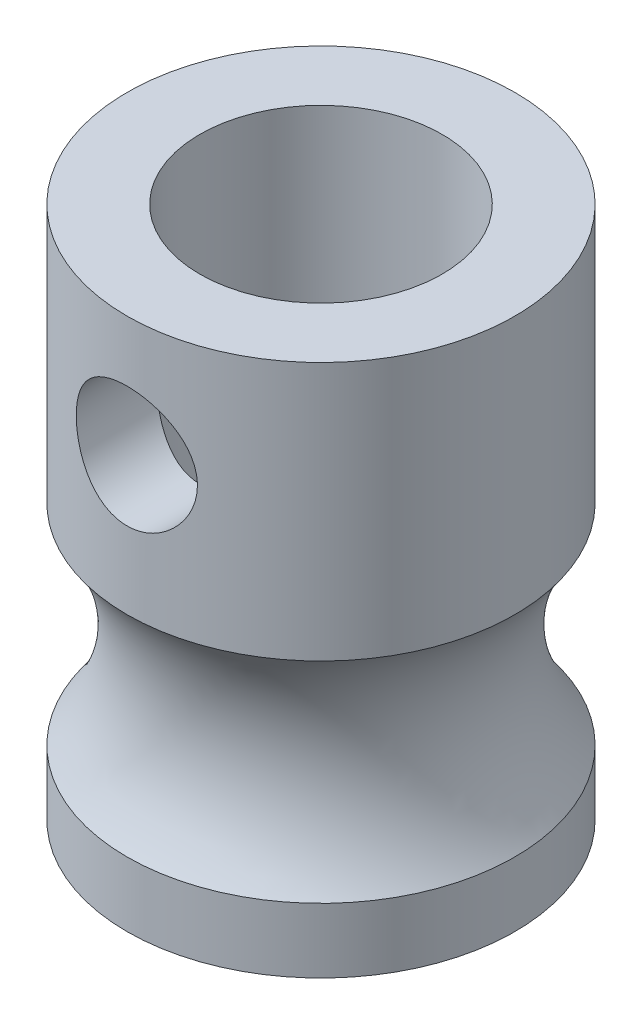
SolidWorks part; units mm, degrees
ref_plane "Front Plane" through (0, 0, 0) normal (0, 0, 1) x (1, 0, 0)
ref_plane "Top Plane" through (0, 0, 0) normal (0, 1, 0) x (1, 0, 0)
ref_plane "Right Plane" through (0, 0, 0) normal (1, 0, 0) x (0, 0, -1)
sketch "Sketch1" plane through (0, 0, 0) normal (0, 1, 0) x (1, 0, 0)
  circle A0 centre (0, 0) radius 4
  circle A1 centre (0, 0) radius 2.5
  dimension "D1" = 8
  dimension "D2" = 5
extrude "Boss-Extrude1" add sketch "Sketch1" along normal blind 11
ref_plane "Plane1" through (0, 0, 4) normal (0, 0, 1) x (1, 0, 0)
ref_axis "Axis1" through (0, 11, 0) along (0, -1, 0)
hole_wizard "M3 Tapped Hole1" positions "Sketch6" profile "Sketch7" tap size "M3" standard "ISO"
sketch "Sketch6" plane through (0, 0, 4) normal (0, 0, 1) x (1, 0, 0)
  line L0 (4, 11) -> (-4, 11) construction
  line L1 (0, 11) -> (0, 0) construction
  point P1 (0, 8.5)
  dimension "D1" = 2.5
cosmetic thread "Hole Thread1" parameters "D2"=3
sketch "Sketch7" plane through (0, 8.5, 4) normal (1, 0, 0) x (0, -1, 0)
  line L0 (0, 0) -> (0, 1.5)
  line L1 (0, 1.5) -> (1.25, 1.5)
  line L2 (1.25, 1.5) -> (1.25, 0)
  line L5 (1.25, 0) -> (0, 0)
  line L11 (0, -6.35) -> (0, 107.95) construction
  dimension "Thru Tap Drill Dia." = 2.5
  dimension "Thru Tap Drill Depth" = 1.5
ref_plane "Plane3" through (0, 0, 0) normal (0, 0, 1) x (1, 0, 0)
sketch "Sketch8" plane through (0, 0, 0) normal (0, 0, 1) x (1, 0, 0)
  line L0 (0, 11) -> (0, 0) construction
  line L1 (4, 11) -> (-4, 11) construction
  circle A0 centre (6.75, 3.5) radius 3.5
  dimension "D1" = 7
  dimension "D2" = 6.75
  dimension "D3" = 7.5
ref_plane "Plane4" through (6.75, 0, 0) normal (1, 0, 0) x (0, 0, -1)
sketch "Sketch9" plane through (6.75, 0, 0) normal (1, 0, 0) x (0, 0, -1)
  line L0 (4.0592, 3.5) -> (-4.0592, 3.5) construction
  circle A0 centre (0, 0) radius 0.5
  dimension "D1" = 1
revolve "Cut-Revolve2" cut sketch "Sketch8" angle 360 about axis through (0, 11, 0) along (0, -1, 0)
